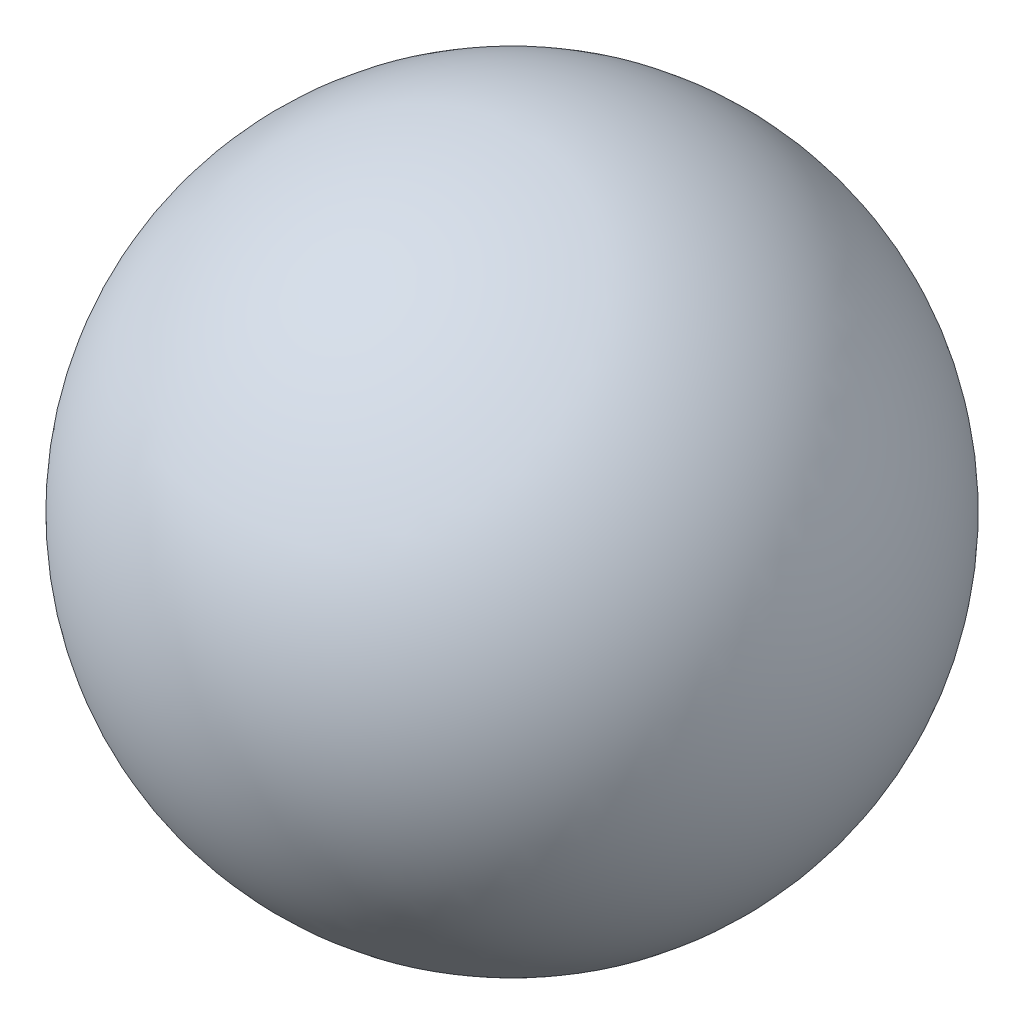
SolidWorks part; units mm, degrees
material "201 軟ｽﾃﾝﾚｽ鋼 (SS)"
ref_plane "正面" through (0, 0, 0) normal (0, 0, 1) x (1, 0, 0)
ref_plane "平面" through (0, 0, 0) normal (0, 1, 0) x (1, 0, 0)
ref_plane "右側面" through (0, 0, 0) normal (1, 0, 0) x (0, 0, -1)
sketch "ｽｹｯﾁ1" plane through (0, 0, 0) normal (0, 0, 1) x (1, 0, 0)
  line L0 (0, 1.985) -> (0, -1.985)
  arc A0 (0, 1.985) -> (0, -1.985) centre (0, 0) cw
  point P4 (0, 2.8306)
  dimension "D1" = 3.97
revolve "回転1" add sketch "ｽｹｯﾁ1" angle 360 about L0
